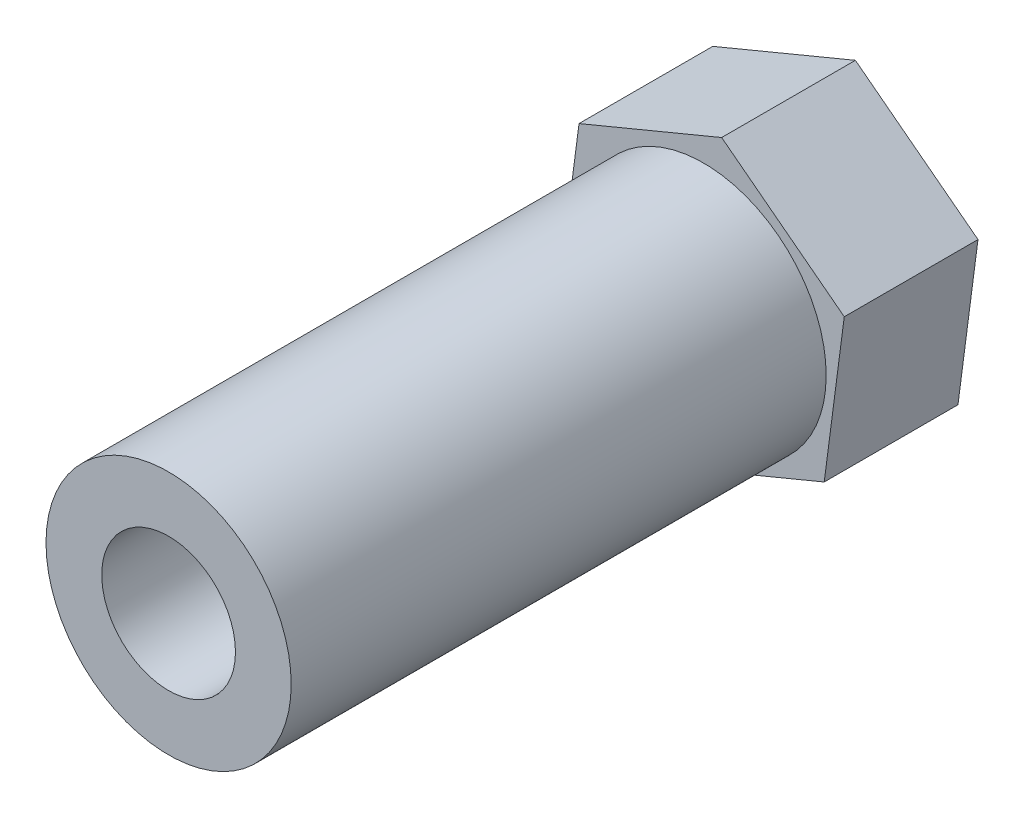
SolidWorks part; units mm, degrees
material "Brass"
ref_plane "Front Plane" through (0, 0, 0) normal (0, 0, 1) x (1, 0, 0)
ref_plane "Top Plane" through (0, 0, 0) normal (0, 1, 0) x (1, 0, 0)
ref_plane "Right Plane" through (0, 0, 0) normal (1, 0, 0) x (0, 0, -1)
sketch "Sketch1" plane through (0, 0, 0) normal (0, 0, 1) x (1, 0, 0)
  line L1 (0.9504, -2.2636) -> (1.8493, 4.6061)
  line L2 (1.8493, 4.6061) -> (-3.6505, 8.8194)
  line L3 (-3.6505, 8.8194) -> (-10.0493, 6.1631)
  line L4 (-10.0493, 6.1631) -> (-10.9482, -0.7066)
  line L5 (-10.9482, -0.7066) -> (-5.4484, -4.9199)
  line L6 (-5.4484, -4.9199) -> (0.9504, -2.2636)
  circle A0 centre (-4.5494, 1.9498) radius 6 construction
  dimension "D1" = 12
extrude "Boss-Extrude1" add sketch "Sketch1" along normal blind 6
sketch "Sketch3" plane through (0, 0, 6) normal (0, 0, 1) x (1, 0, 0)
  circle A0 centre (-4.4621, 1.9253) radius 5.5
  dimension "D1" = 11
extrude "Boss-Extrude2" add sketch "Sketch3" along normal blind 24
sketch "Sketch4" plane through (0, 0, 0) normal (0, 0, -1) x (-1, 0, 0)
  circle A0 centre (4.4621, 1.9253) radius 1.5
  circle A1 centre (4.4621, 1.9253) radius 5.5 construction
  dimension "D1" = 3
  dimension "D2" = 0
extrude "Cut-Extrude1" cut sketch "Sketch4" against normal blind 6
sketch "Sketch5" plane through (0, 0, 30) normal (0, 0, 1) x (1, 0, 0)
  circle A0 centre (-4.4621, 1.9253) radius 3
  circle A2 centre (-4.4621, 1.9253) radius 5.5 construction
  point P4 (-4.4621, 1.7926)
  point P5 (-4.4621, 1.7926)
  dimension "D2" = 6
  dimension "D1" = 0
extrude "Cut-Extrude2" cut sketch "Sketch5" against normal blind 24
